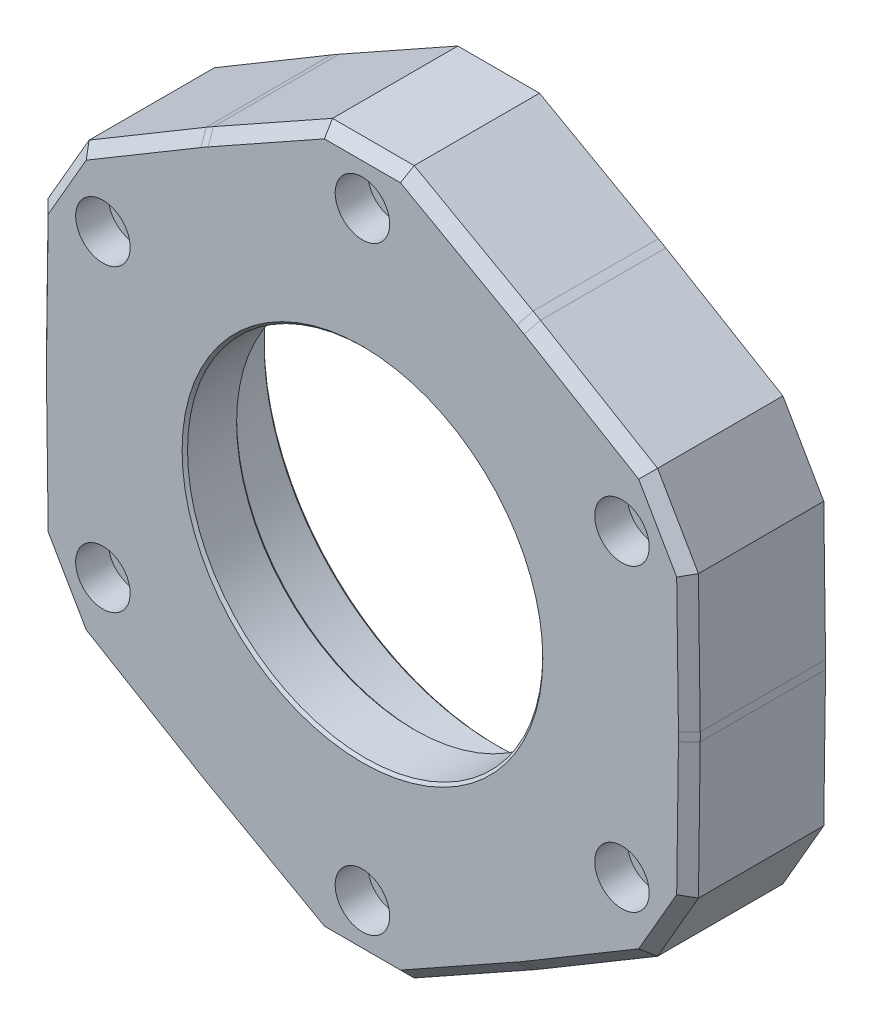
SolidWorks part; units mm, degrees
ref_plane "Front Plane" through (0, 0, 0) normal (0, 0, 1) x (1, 0, 0)
ref_plane "Top Plane" through (0, 0, 0) normal (0, 1, 0) x (1, 0, 0)
ref_plane "Right Plane" through (0, 0, 0) normal (1, 0, 0) x (0, 0, -1)
sketch "Sketch1" plane through (0, 0, 0) normal (0, 0, 1) x (1, 0, 0)
  circle A0 centre (0, 0) radius 60
  circle A1 centre (0, 0) radius 55 construction
  circle A2 centre (0, 55) radius 2.55
  circle A3 centre (47.6314, 27.5) radius 2.55
  circle A4 centre (47.6314, -27.5) radius 2.55
  circle A5 centre (0, -55) radius 2.55
  circle A6 centre (-47.6314, -27.5) radius 2.55
  circle A7 centre (-47.6314, 27.5) radius 2.55
  circle A8 centre (0, 0) radius 42.55
  point P18 (0, 0)
  dimension "D1" = 120
  dimension "D2" = 110
  dimension "D3" = 5.1
  dimension "D5" = 85.1
  dimension "D4" = 6
extrude "Boss-Extrude1" add sketch "Sketch1" along normal blind 25
sketch "Sketch3" plane through (0, 0, 25) normal (0, 0, 1) x (1, 0, 0)
  circle A0 centre (0, 0) radius 42.55
  circle A1 centre (0, 0) radius 32.6
  dimension "D1" = 85.1
  dimension "D2" = 65.2
extrude "Boss-Extrude2" add sketch "Sketch3" against normal blind 10
sketch "Sketch7" plane through (0, 0, 0) normal (0, 0, -1) x (-1, 0, 0)
  line L0 (-29.3133, 52.352) -> (-7.5, 64.5659)
  line L1 (-7.5, 64.5659) -> (7.5, 64.5659)
  line L2 (7.5, 64.5659) -> (29.3133, 52.352)
  line L3 (59.6657, 25.7877) -> (59.9948, 0.7899)
  line L4 (52.1657, 38.7781) -> (59.6657, 25.7877)
  line L5 (30.6815, 51.5621) -> (52.1657, 38.7781)
  line L6 (52.1657, -38.7781) -> (30.6815, -51.5621)
  line L7 (59.6657, -25.7877) -> (52.1657, -38.7781)
  line L8 (59.9948, -0.7899) -> (59.6657, -25.7877)
  line L9 (-7.5, -64.5659) -> (-29.3133, -52.352)
  line L10 (7.5, -64.5659) -> (-7.5, -64.5659)
  line L11 (29.3133, -52.352) -> (7.5, -64.5659)
  line L12 (-59.6657, -25.7877) -> (-59.9948, -0.7899)
  line L13 (-52.1657, -38.7781) -> (-59.6657, -25.7877)
  line L14 (-30.6815, -51.5621) -> (-52.1657, -38.7781)
  line L15 (-52.1657, 38.7781) -> (-30.6815, 51.5621)
  line L16 (-59.6657, 25.7877) -> (-52.1657, 38.7781)
  line L17 (-59.9948, 0.7899) -> (-59.6657, 25.7877)
  circle A0 centre (0, 0) radius 65 construction
  circle A1 centre (0, 0) radius 60 construction
  arc A2 (-30.6815, 51.5621) -> (-59.9948, 0.7899) centre (0, 0) ccw
  arc A3 (29.3133, 52.352) -> (-29.3133, 52.352) centre (0, 0) ccw
  arc A4 (59.9948, 0.7899) -> (30.6815, 51.5621) centre (0, 0) ccw
  arc A5 (30.6815, -51.5621) -> (59.9948, -0.7899) centre (0, 0) ccw
  arc A6 (-29.3133, -52.352) -> (29.3133, -52.352) centre (0, 0) ccw
  arc A7 (-59.9948, -0.7899) -> (-30.6815, -51.5621) centre (0, 0) ccw
  point P8 (0, 64.5659)
  point P35 (0, 0)
  dimension "D1" = 130
  dimension "D2" = 15
  dimension "D3" = 6
extrude "Boss-Extrude3" add sketch "Sketch7" against normal up to surface (25 mm away) up to face at (-45.0814, -27.5, 25)
sketch "Sketch8" plane through (0, 0, 25) normal (0, 0, 1) x (1, 0, 0)
  circle A0 centre (0, 55) radius 5
  circle A1 centre (47.6314, 27.5) radius 5
  circle A2 centre (47.6314, -27.5) radius 5
  circle A3 centre (0, -55) radius 5
  circle A4 centre (-47.6314, -27.5) radius 5
  circle A5 centre (-47.6314, 27.5) radius 5
  point P15 (0, 0)
  dimension "D1" = 10
  dimension "D2" = 6
extrude "Cut-Extrude1" cut sketch "Sketch8" against normal blind 6
chamfer "Chamfer2" distance 0.5 angle 45 3 edges at (42.55, 0, 0) (32.6, 0, 15) (32.6, 0, 25)
chamfer "Chamfer3" distance 2 angle 45 24 edges at (-18.4067, 58.4589, 25) (0, 64.5659, 25) (18.4067, 58.4589, 25) (30, 51.9615, 25) (41.4236, 45.1701, 25) (55.9157, 32.2829, 25) (59.8302, 13.2888, 25) (60, 0, 25) (59.8302, -13.2888, 25) (55.9157, -32.2829, 25) (41.4236, -45.1701, 25) (30, -51.9615, 25) (18.4067, -58.4589, 25) (0, -64.5659, 25) (-18.4067, -58.4589, 25) (-30, -51.9615, 25) (-41.4236, -45.1701, 25) (-55.9157, -32.2829, 25) (-59.8302, -13.2888, 25) (-60, 0, 25) (-59.8302, 13.2888, 25) (-55.9157, 32.2829, 25) (-41.4236, 45.1701, 25) (-30, 51.9615, 25)
sketch "Sketch9" plane through (0, 0, 0) normal (0, 0, -1) x (-1, 0, 0)
  line L0 (0, 47.96) -> (0, 0) construction
  line L1 (0, 0) -> (-8.3282, 47.2314) construction
  circle A55 centre (0, 0) radius 47.96 construction
  circle A56 centre (-8.3282, 47.2314) radius 2.025
  circle A57 centre (8.3282, 47.2314) radius 2.025
  circle A58 centre (23.98, 41.5346) radius 2.025
  circle A59 centre (36.7395, 30.8281) radius 2.025
  circle A60 centre (45.0677, 16.4033) radius 2.025
  circle A61 centre (47.96, 0) radius 2.025
  circle A62 centre (45.0677, -16.4033) radius 2.025
  circle A63 centre (36.7395, -30.8281) radius 2.025
  circle A64 centre (23.98, -41.5346) radius 2.025
  circle A65 centre (8.3282, -47.2314) radius 2.025
  circle A66 centre (-8.3282, -47.2314) radius 2.025
  circle A67 centre (-23.98, -41.5346) radius 2.025
  circle A68 centre (-36.7395, -30.8281) radius 2.025
  circle A69 centre (-45.0677, -16.4033) radius 2.025
  circle A70 centre (-47.96, 0) radius 2.025
  circle A71 centre (-45.0677, 16.4033) radius 2.025
  circle A72 centre (-36.7395, 30.8281) radius 2.025
  circle A73 centre (-23.98, 41.5346) radius 2.025
  point P42 (0, 0)
  point P61 (0, 0)
  point P96 (0, 0)
  dimension "D1" = 95.92
  dimension "D3" = 4.05
  dimension "D4" = 18
  dimension "D2" = 10
extrude "Cut-Extrude2" cut sketch "Sketch9" against normal blind 7
